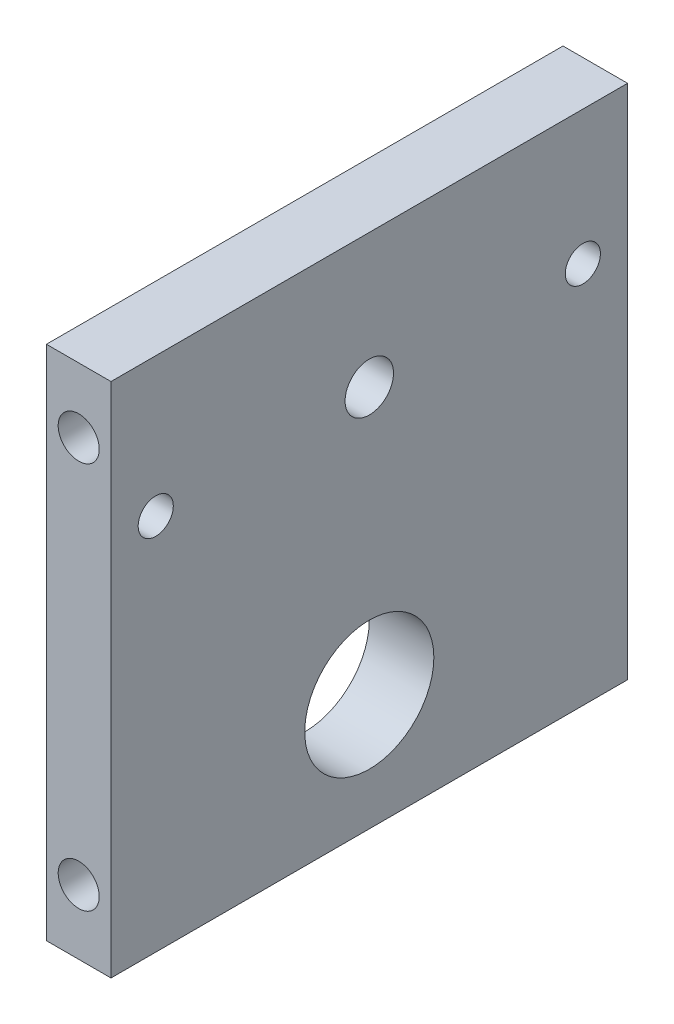
SolidWorks part; units mm, degrees
ref_plane "Front Plane" through (0, 0, 0) normal (0, 0, 1) x (1, 0, 0)
ref_plane "Top Plane" through (0, 0, 0) normal (0, 1, 0) x (1, 0, 0)
ref_plane "Right Plane" through (0, 0, 0) normal (1, 0, 0) x (0, 0, -1)
sketch "Sketch1" plane through (0, 0, 0) normal (1, 0, 0) x (0, 0, -1)
  line L1 (-25.4, -25.4) -> (25.4, -25.4)
  line L2 (-25.4, -25.4) -> (-25.4, 25.4)
  line L3 (-25.4, 25.4) -> (25.4, 25.4)
  line L4 (25.4, -25.4) -> (25.4, 25.4)
  line L5 (-25.4, -25.4) -> (25.4, 25.4) construction
  line L6 (-25.4, 25.4) -> (25.4, -25.4) construction
  point P0 (0, 0)
  dimension "D1" = 50.8
  dimension "D2" = 50.8
extrude "Boss-Extrude1" add sketch "Sketch1" along normal blind 6.35
hole_wizard "1/2 (0.5) Diameter Hole1" positions "Sketch9" profile "Sketch8" hole size "1/2" standard "ANSI Inch"
sketch "Sketch9" plane through (6.35, 0, 0) normal (1, 0, 0) x (0, 0, -1)
  line L0 (-25.4, -25.4) -> (25.4, -25.4) construction
  point P0 (0, -13.97)
  dimension "D1" = 11.43
sketch "Sketch8" plane through (6.35, -13.97, 0) normal (0, 1, 0) x (0, 0, -1)
  line L0 (0, 0) -> (0, 73.9195)
  line L1 (0, 73.9195) -> (6.35, 70.104)
  line L2 (6.35, 70.104) -> (6.35, 0)
  line L5 (6.35, 0) -> (0, 0)
  line L10 (0, 73.9195) -> (-6.35, 70.104) construction
  line L11 (0, -6.35) -> (0, 107.95) construction
  dimension "Hole Dia." = 12.7
  dimension "Hole Depth" = 70.104
  dimension "Drill Angle" = 118
hole_wizard "3/16 (0.1875) Diameter Hole1" positions "Sketch3" profile "Sketch2" hole size "3/16" standard "ANSI Inch"
sketch "Sketch3" plane through (6.35, 0, 0) normal (1, 0, 0) x (0, 0, -1)
  circle A0 centre (0, -13.97) radius 6.35 construction
  point P0 (0, 12.2301)
  dimension "D1" = 26.2001
  dimension "D2" = 0
sketch "Sketch2" plane through (6.35, 12.2301, 0) normal (0, 1, 0) x (0, 0, -1)
  line L0 (0, 0) -> (0, 71.5348)
  line L1 (0, 71.5348) -> (2.3812, 70.104)
  line L2 (2.3812, 70.104) -> (2.3812, 0)
  line L5 (2.3812, 0) -> (0, 0)
  line L10 (0, 71.5348) -> (-2.3813, 70.104) construction
  line L11 (0, -6.35) -> (0, 107.95) construction
  dimension "Hole Dia." = 4.7625
  dimension "Hole Depth" = 70.104
  dimension "Drill Angle" = 118
hole_wizard "#29 (0.136) Diameter Hole1" positions "Sketch5" profile "Sketch4" hole size "#29" standard "ANSI Inch"
sketch "Sketch5" plane through (6.35, 0, 0) normal (1, 0, 0) x (0, 0, -1)
  circle A0 centre (0, 12.2301) radius 2.3812 construction
  point P0 (21, 12.2301)
  point P2 (-21, 11.7415)
  dimension "D1" = 0.4886
  dimension "D2" = 0
  dimension "D3" = 21
  dimension "D4" = 42
sketch "Sketch4" plane through (6.35, 12.2301, -21) normal (0, 1, 0) x (0, 0, -1)
  line L0 (0, 0) -> (0, 71.1418)
  line L1 (0, 71.1418) -> (1.7272, 70.104)
  line L2 (1.7272, 70.104) -> (1.7272, 0)
  line L5 (1.7272, 0) -> (0, 0)
  line L10 (0, 71.1418) -> (-1.7272, 70.104) construction
  line L11 (0, -6.35) -> (0, 107.95) construction
  dimension "Hole Dia." = 3.4544
  dimension "Hole Depth" = 70.104
  dimension "Drill Angle" = 118
hole_wizard "#10-32 Tapped Hole1" positions "Sketch11" profile "Sketch10" tap size "#10-32" standard "ANSI Inch"
sketch "Sketch11" plane through (-0.103, -5.3339, 25.4) normal (0, 0, -1) x (-1, 0, 0)
  line L0 (-6.453, 30.7339) -> (-0.103, 30.7339) construction
  line L2 (-6.453, -20.0661) -> (-0.103, -20.0661) construction
  line L3 (-6.453, 30.7339) -> (-0.103, 30.7339) construction
  point P0 (-3.278, -13.7161)
  point P2 (-3.278, 24.3839)
  point P6 (-3.278, 30.7339)
  dimension "D1" = 0
  dimension "D2" = 0
  dimension "D3" = 6.35
  dimension "D4" = 6.35
sketch "Sketch10" plane through (3.175, -19.05, 25.4) normal (1, 0, 0) x (0, -1, 0)
  line L0 (0, 0) -> (0, 13.1513)
  line L1 (0, 13.1513) -> (2.0193, 11.938)
  line L2 (2.0193, 11.938) -> (2.0193, 0)
  line L5 (2.0193, 0) -> (0, 0)
  line L10 (0, 13.1513) -> (-2.0193, 11.938) construction
  line L11 (0, -6.35) -> (0, 107.95) construction
  dimension "Tap Drill Dia." = 4.0386
  dimension "Tap Drill Depth" = 11.938
  dimension "Drill Angle" = 118
cosmetic thread "Hole Thread1"
cosmetic thread "Hole Thread2"
